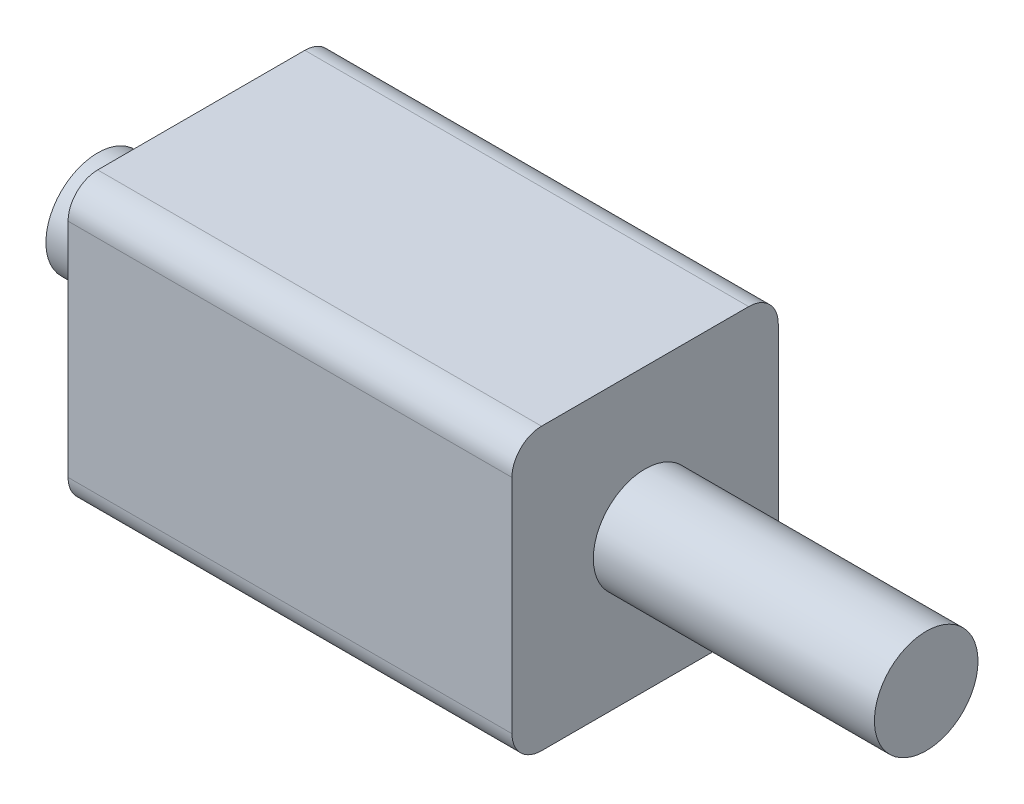
SolidWorks part; units mm, degrees
ref_plane "Front Plane" through (0, 0, 0) normal (0, 0, 1) x (1, 0, 0)
ref_plane "Top Plane" through (0, 0, 0) normal (0, 1, 0) x (1, 0, 0)
ref_plane "Right Plane" through (0, 0, 0) normal (1, 0, 0) x (0, 0, -1)
sketch "Sketch1" plane through (0, 0, 0) normal (0, 1, 0) x (1, 0, 0)
  line L1 (-15, -9) -> (15, -9)
  line L2 (-15, -9) -> (-15, 9)
  line L3 (-15, 9) -> (15, 9)
  line L4 (15, -9) -> (15, 9)
  line L5 (-15, -9) -> (15, 9) construction
  line L6 (-15, 9) -> (15, -9) construction
  point P0 (0, 0)
  dimension "D1" = 30
  dimension "D2" = 18
extrude "Boss-Extrude1" add sketch "Sketch1" along normal blind 19
sketch "Sketch2" plane through (15, 0, 0) normal (1, 0, 0) x (0, 0, -1)
  line L0 (9, 19) -> (9, 0) construction
  line L1 (-9, 0) -> (9, 0) construction
  circle A0 centre (0, 9.5) radius 3.5
  point P4 (9, 9.5)
  point P7 (0, 0)
  dimension "D1" = 7
extrude "Boss-Extrude2" add sketch "Sketch2" along normal blind 19 and the other way blind 37
fillet "Fillet1" radius 2 4 edges at (0, 19, -9) (0, 19, 9) (0, 0, 9) (0, 0, -9)
